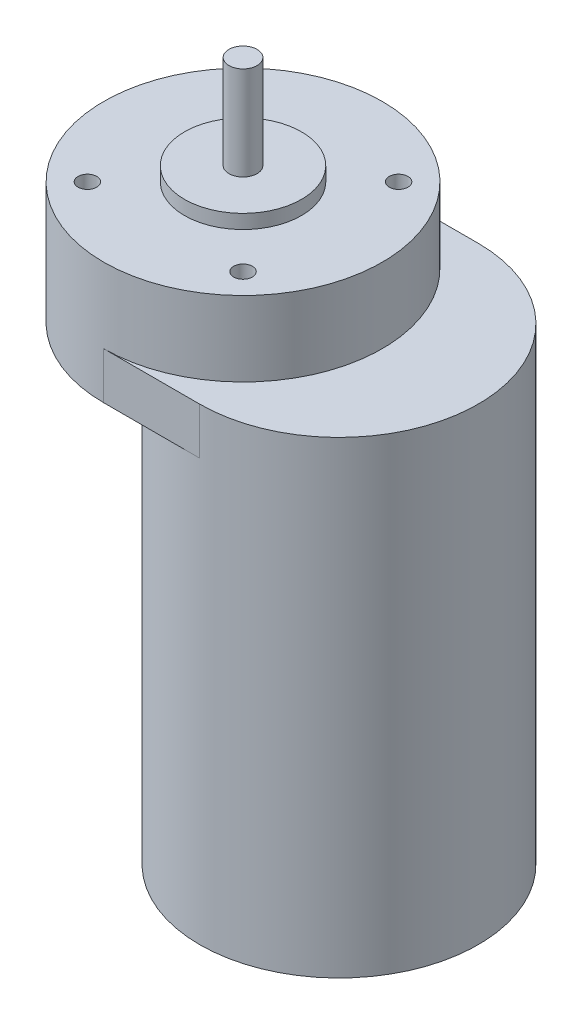
SolidWorks part; units mm, degrees
ref_plane "Front Plane" through (0, 0, 0) normal (0, 0, 1) x (1, 0, 0)
ref_plane "Top Plane" through (0, 0, 0) normal (0, 1, 0) x (1, 0, 0)
ref_plane "Right Plane" through (0, 0, 0) normal (1, 0, 0) x (0, 0, -1)
sketch "Sketch1" plane through (0, 0, 0) normal (0, 1, 0) x (1, 0, 0)
  circle A0 centre (0, 0) radius 29.75
  dimension "D1" = 59.5
extrude "Boss-Extrude1" add sketch "Sketch1" along normal blind 90
sketch "Sketch2" plane through (0, 90, 0) normal (0, 1, 0) x (1, 0, 0)
  line L0 (0, 0) -> (-20.5, 0) construction
  line L1 (0, -29.75) -> (-20.5, -29.75)
  line L2 (0, 29.75) -> (-20.5, 29.75)
  arc A0 (0, -29.75) -> (0, 29.75) centre (0, 0) ccw
  arc A1 (-20.5, 29.75) -> (-20.5, -29.75) centre (-20.5, 0) ccw
  point P3 (-10.25, 0)
  point P8 (-50.25, 0)
  point P9 (29.75, 0)
  dimension "D1" = 29.75
  dimension "D2" = 80
extrude "Boss-Extrude2" add sketch "Sketch2" along normal blind 10
sketch "Sketch3" plane through (0, 100, 0) normal (0, 1, 0) x (1, 0, 0)
  circle A0 centre (-20.5, 0) radius 29.75
  arc A1 (-20.5, 29.75) -> (-20.5, -29.75) centre (-20.5, 0) ccw construction
  dimension "D1" = 59.5
extrude "Boss-Extrude3" add sketch "Sketch3" along normal blind 16
sketch "Sketch4" plane through (0, 116, 0) normal (0, 1, 0) x (1, 0, 0)
  circle A0 centre (-20.5, 0) radius 12.5
  circle A1 centre (-20.5, 0) radius 3
  dimension "D1" = 25
  dimension "D2" = 6
extrude "Boss-Extrude4" add sketch "Sketch4" along normal blind 3
sketch "Sketch7" plane through (0, 119, 0) normal (0, 1, 0) x (1, 0, 0)
  circle A0 centre (-20.5, 0) radius 3
extrude "Boss-Extrude5" add sketch "Sketch7" along normal blind 20 separate body
sketch "Sketch8" plane through (0, 116, 0) normal (0, 1, 0) x (1, 0, 0)
  line L0 (-37.117, 16.617) -> (-3.883, -16.617) construction
  line L1 (-20.5, 0) -> (-14.5333, 0) construction
  circle A0 centre (-20.5, 0) radius 23.5 construction
  circle A1 centre (-37.117, 16.617) radius 2
  circle A2 centre (-37.117, -16.617) radius 2
  circle A3 centre (-3.883, -16.617) radius 2
  circle A4 centre (-3.883, 16.617) radius 2
  point P17 (-20.5, 0)
  dimension "D1" = 47
  dimension "D3" = 4
  dimension "D2" = 135
  dimension "D4" = 4
extrude "Cut-Extrude1" cut sketch "Sketch8" against normal blind 20
